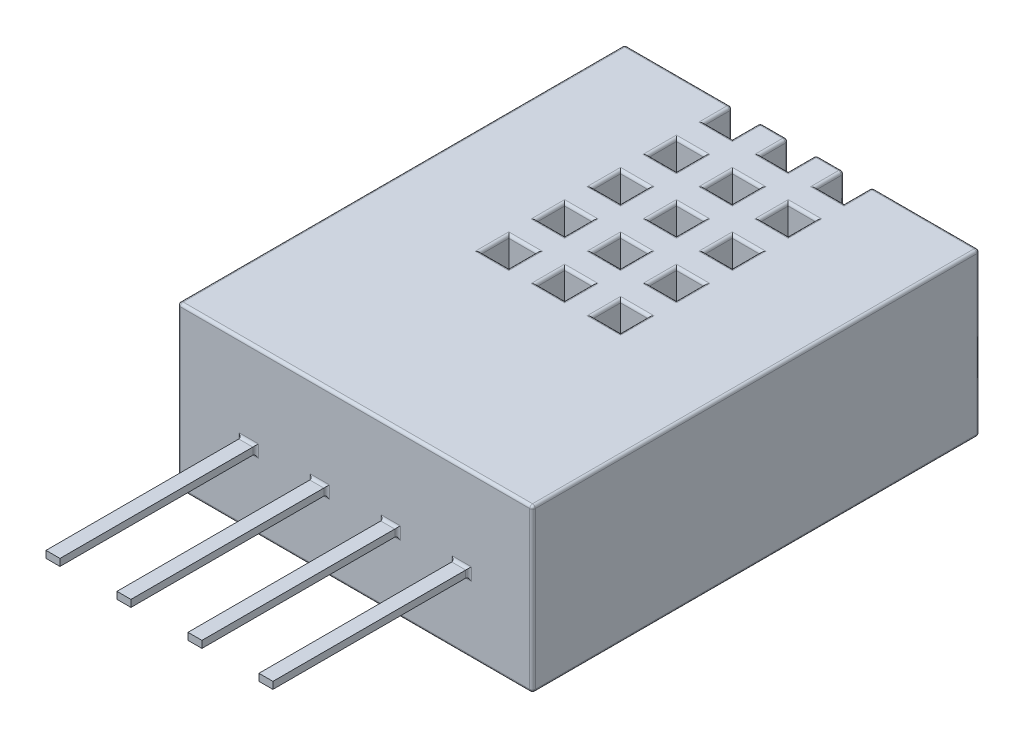
SolidWorks part; units mm, degrees
ref_plane "Front Plane" through (0, 0, 0) normal (0, 0, 1) x (1, 0, 0)
ref_plane "Top Plane" through (0, 0, 0) normal (0, 1, 0) x (1, 0, 0)
ref_plane "Right Plane" through (0, 0, 0) normal (1, 0, 0) x (0, 0, -1)
sketch "Sketch1" plane through (0, 0, 0) normal (0, 1, 0) x (1, 0, 0)
  line L1 (-6.35, -8) -> (6.35, -8)
  line L2 (-6.35, -8) -> (-6.35, 8)
  line L3 (-6.35, 8) -> (6.35, 8)
  line L4 (6.35, -8) -> (6.35, 8)
  line L5 (-6.35, -8) -> (6.35, 8) construction
  line L6 (-6.35, 8) -> (6.35, -8) construction
  point P0 (0, 0)
  dimension "D1" = 12.7
  dimension "D2" = 16
extrude "Boss-Extrude1" add sketch "Sketch1" along normal blind 5.8
sketch "Sketch2" plane through (0, 5.8, 0) normal (0, 1, 0) x (1, 0, 0)
  line L0 (6.35, 8) -> (-6.35, 8) construction
  line L1 (-0.5, 8) -> (0.5, 8)
  line L2 (-0.5, 8) -> (-0.5, 7)
  line L3 (-0.5, 7) -> (0.5, 7)
  line L4 (0.5, 8) -> (0.5, 7)
  line L5 (-0.5, 8) -> (0.5, 7) construction
  line L6 (-0.5, 7) -> (0.5, 8) construction
  line L11 (-0.5, 8) -> (-0.5, 7)
  line L12 (-0.5, 8) -> (0.5, 8)
  line L13 (0.5, 8) -> (0.5, 7)
  line L14 (-0.5, 7) -> (0.5, 7)
  point P0 (0, 7.5)
  line M31 (6.35, 8) -> (-6.35, 8)
  dimension "D1" = 1
extrude "Cut-Extrude2" cut sketch "Sketch2" against normal blind 2 contours L4 L2 L3 M31
pattern_linear "LPattern1" count 5 spacing 2 along (0, 0, 1) of "Cut-Extrude2"
pattern_linear "LPattern2" count 2 spacing 2 along (-1, 0, 0) count 2 spacing 2 along (1, 0, 0) of "LPattern1", "Cut-Extrude2"
sketch "Sketch3" plane through (0, 0, 8) normal (0, 0, 1) x (1, 0, 0)
  line L0 (-1.52, 2.75) -> (-1.52, 2.5)
  line L1 (-4.06, 2.75) -> (-3.56, 2.75)
  line L2 (-4.06, 2.75) -> (-4.06, 2.5)
  line L3 (-4.06, 2.5) -> (-3.56, 2.5)
  line L4 (-3.56, 2.75) -> (-3.56, 2.5)
  line L5 (-4.06, 2.75) -> (-3.56, 2.5) construction
  line L6 (-4.06, 2.5) -> (-3.56, 2.75) construction
  line L7 (-1.52, 2.75) -> (-1.02, 2.75)
  line L8 (-1.02, 2.75) -> (-1.02, 2.5)
  line L9 (-1.52, 2.5) -> (-1.02, 2.5)
  line L10 (-1.52, 2.5) -> (-1.02, 2.75) construction
  line L11 (-1.52, 2.75) -> (-1.02, 2.5) construction
  line L12 (1.02, 2.75) -> (1.02, 2.5)
  line L13 (1.02, 2.75) -> (1.52, 2.75)
  line L14 (1.52, 2.75) -> (1.52, 2.5)
  line L15 (1.02, 2.5) -> (1.52, 2.5)
  line L16 (1.02, 2.5) -> (1.52, 2.75) construction
  line L17 (1.02, 2.75) -> (1.52, 2.5) construction
  line L18 (3.56, 2.75) -> (3.56, 2.5)
  line L19 (3.56, 2.75) -> (4.06, 2.75)
  line L20 (4.06, 2.75) -> (4.06, 2.5)
  line L21 (3.56, 2.5) -> (4.06, 2.5)
  line L22 (3.56, 2.5) -> (4.06, 2.75) construction
  line L23 (3.56, 2.75) -> (4.06, 2.5) construction
  line L24 (-1.27, 2.625) -> (1.27, 2.625) construction
  line L25 (-6.35, 0) -> (6.35, 0) construction
  point P0 (-3.81, 2.625)
  point P7 (-1.27, 2.625)
  point P12 (1.27, 2.625)
  point P17 (3.81, 2.625)
  point P22 (0, 2.625)
  point P26 (0, 0)
  dimension "D1" = 0.5
  dimension "D2" = 0.25
  dimension "D4" = 2.5
  dimension "D5" = 2.54
  dimension "D3" = 4
extrude "Boss-Extrude2" add sketch "Sketch3" along normal blind 7
fillet "Fillet1" radius 0.1 97 edges at (2.5, 5.8, -7.5) (2.5, 4.8, -8) (2, 3.8, -8) (1.5, 4.8, -8) (1.5, 5.8, -7.5) (2, 5.8, -7) (2.5, 5.8, -5.5) (2, 5.8, -6) (1.5, 5.8, -5.5) (2, 5.8, -5) (2.5, 5.8, -3.5) (2, 5.8, -4) (1.5, 5.8, -3.5) (2, 5.8, -3) (2.5, 5.8, -1.5) (-6.35, 5.8, 0) (2, 5.8, -2) (1.5, 5.8, -1.5) (2, 5.8, -1) (2.5, 5.8, 0.5) (2, 5.8, 0) (1.5, 5.8, 0.5) (2, 5.8, 1) (-1, 5.8, -8) (-4.425, 5.8, -8) (0, 5.8, 8) (-1.5, 5.8, -7.5) (-1.5, 4.8, -8) (-2, 3.8, -8) (-2.5, 4.8, -8) (-2.5, 5.8, -7.5) (-2, 5.8, -7) (-1.5, 5.8, -5.5) (0.5, 5.8, -7.5) (-2, 5.8, -6) (-2.5, 5.8, -5.5) (-2, 5.8, -5) (0.5, 4.8, -8) (-1.5, 5.8, -3.5) (-2, 5.8, -4) (-2.5, 5.8, -3.5) (-2, 5.8, -3) (-1.5, 5.8, -1.5) (0, 3.8, -8) (-2, 5.8, -2) (-2.5, 5.8, -1.5) (-2, 5.8, -1) (-0.5, 4.8, -8) (-1.5, 5.8, 0.5) (-2, 5.8, 0) (-2.5, 5.8, 0.5) (-2, 5.8, 1) (-0.5, 5.8, -7.5) (0, 5.8, -7) (-3.56, 2.625, 8) (-3.81, 2.75, 8) (-4.06, 2.625, 8) (-3.81, 2.5, 8) (-1.27, 2.5, 8) (-1.02, 2.625, 8) (-1.27, 2.75, 8) (-1.52, 2.625, 8) (1.27, 2.5, 8) (1.52, 2.625, 8) (1.27, 2.75, 8) (1.02, 2.625, 8) (3.81, 2.5, 8) (4.06, 2.625, 8) (3.81, 2.75, 8) (3.56, 2.625, 8) (0.5, 5.8, -5.5) (0, 5.8, -6) (-0.5, 5.8, -5.5) (0, 5.8, -5) (0.5, 5.8, -3.5) (0, 5.8, -4) (-0.5, 5.8, -3.5) (0, 5.8, -3) (6.35, 5.8, 0) (0, 0, 8) (0.5, 5.8, -1.5) (0, 5.8, -2) (-6.35, 0, 0) (-0.5, 5.8, -1.5) (0, 5.8, -1) (0, 0, -8) (0.5, 5.8, 0.5) (0, 5.8, 0) (-0.5, 5.8, 0.5) (0, 5.8, 1) (6.35, 0, 0) (6.35, 2.9, 8) (-6.35, 2.9, 8) (-6.35, 2.9, -8) (6.35, 2.9, -8) (4.425, 5.8, -8) (1, 5.8, -8)
